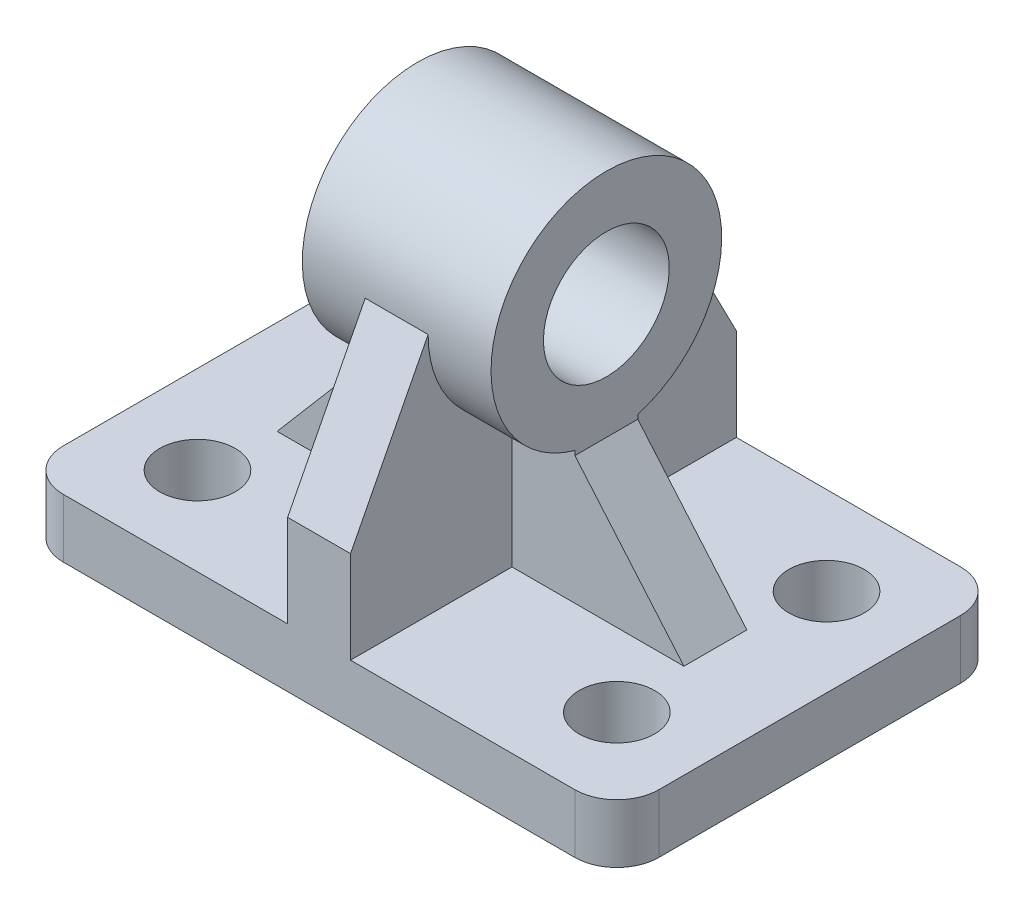
SolidWorks part; units mm, degrees
ref_plane "Front Plane" through (0, 0, 0) normal (0, 0, 1) x (1, 0, 0)
ref_plane "Top Plane" through (0, 0, 0) normal (0, 1, 0) x (1, 0, 0)
ref_plane "Right Plane" through (0, 0, 0) normal (1, 0, 0) x (0, 0, -1)
sketch "Sketch1" plane through (0, 0, 0) normal (0, 1, 0) x (1, 0, 0)
  line L1 (-71, 46) -> (71, 46)
  line L2 (-71, 46) -> (-71, -46)
  line L3 (-71, -46) -> (71, -46)
  line L4 (71, 46) -> (71, -46)
  point P4 (0, -46)
  point P6 (71, 0)
  dimension "D1" = 92
  dimension "D2" = 142
extrude "Boss-Extrude1" add sketch "Sketch1" along normal blind 14
fillet "Fillet1" radius 10 4 edges at (-71, 7, -46) (71, 7, -46) (-71, 7, 46) (71, 7, 46)
sketch "Sketch2" plane through (0, 0, 0) normal (1, 0, 0) x (0, 0, -1)
  line L0 (-36, 14) -> (36, 14) construction
  circle A0 centre (0, 72) radius 15
  circle A1 centre (0, 72) radius 27.5
  dimension "D1" = 30
  dimension "D2" = 55
  dimension "D3" = 58
extrude "Boss-Extrude2" add sketch "Sketch2" along normal mid plane 45 separate body
sketch "Sketch3" plane through (0, 0, 0) normal (0, 0, 1) x (1, 0, 0)
  line L1 (0, 49.5) -> (-22.5, 49.5)
  line L2 (-22.5, 44.5) -> (-48.5, 14)
  line L3 (-61, 14) -> (61, 14) construction
  line L4 (-48.5, 14) -> (-48.5, 6.53)
  line L5 (-48.5, 6.53) -> (0, 6.53)
  line L6 (0, 6.53) -> (0, 44.5)
  line L7 (-22.5, 44.5) -> (22.5, 44.5) construction
  line L9 (0, 44.5) -> (0, 49.5)
  line L10 (-22.5, 44.5) -> (-22.5, 49.5)
  dimension "D1" = 48.5
extrude "Boss-Extrude3" add sketch "Sketch3" along normal mid plane 15
mirror "Mirror1" about plane through (0, 0, 0) normal (1, 0, 0) of bodies 103
sketch "Sketch4" plane through (0, 0, 0) normal (1, 0, 0) x (0, 0, -1)
  line L0 (-36, 14) -> (36, 14) construction
  line L1 (7.5, 14) -> (36, 14)
  line L2 (36, 14) -> (46, 14)
  line L3 (-7.5, 45.5425) -> (-7.5, 44.5)
  line L4 (-7.5, 44.5) -> (7.5, 44.5)
  line L5 (7.5, 44.5) -> (7.5, 45.5425)
  line L8 (7.5, 44.5) -> (7.5, 45.5425)
  line L9 (46, 14) -> (46, 36)
  line L10 (46, 36) -> (27.5, 72)
  line L11 (7.5, 44.5) -> (7.5, 14)
  arc A1 (7.5, 45.5425) -> (-7.5, 45.5425) centre (0, 72) ccw
  arc A2 (7.5, 45.5425) -> (27.5, 72) centre (0, 72) ccw
  dimension "D2" = 22
  dimension "D1" = 0
extrude "Boss-Extrude4" add sketch "Sketch4" along normal mid plane 15
mirror "Mirror3" about plane through (0, 0, 0) normal (0, 0, 1) of bodies 105
sketch "Sketch5" plane through (0, 14, 0) normal (0, 1, 0) x (1, 0, 0)
  line L0 (22.5, -27.5) -> (22.5, 27.5) construction
  line L1 (61, 46) -> (7.5, 46) construction
  line L2 (0, 57.138) -> (0, -20.7165) construction
  circle A0 centre (50, -25) radius 9
  circle A1 centre (50, 25) radius 9
  circle A2 centre (-50, 25) radius 9
  circle A3 centre (-50, -25) radius 9
  dimension "D1" = 18
  dimension "D2" = 27.5
  dimension "D3" = 27.5
  dimension "D4" = 21
  dimension "D5" = 50
extrude "Cut-Extrude1" cut sketch "Sketch5" against normal through all
